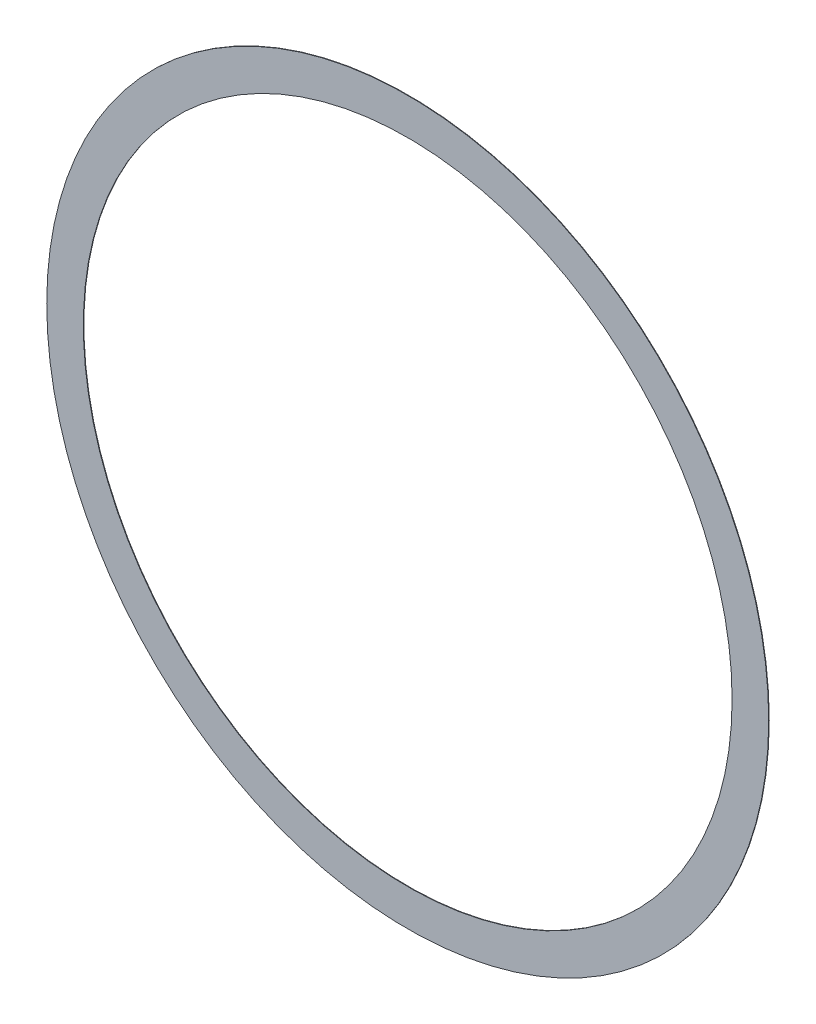
SolidWorks part; units mm, degrees
material "M/S SHIM"
ref_plane "Front Plane" through (0, 0, 0) normal (0, 0, 1) x (1, 0, 0)
ref_plane "Top Plane" through (0, 0, 0) normal (0, 1, 0) x (1, 0, 0)
ref_plane "Right Plane" through (0, 0, 0) normal (1, 0, 0) x (0, 0, -1)
sketch "Sketch1" plane through (0, 0, 0) normal (0, 0, 1) x (1, 0, 0)
  circle A0 centre (0, 0) radius 69
  circle A1 centre (0, 0) radius 62
  dimension "D1" = 138
  dimension "D2" = 124
extrude "Boss-Extrude1" add sketch "Sketch1" along normal blind 0.1
